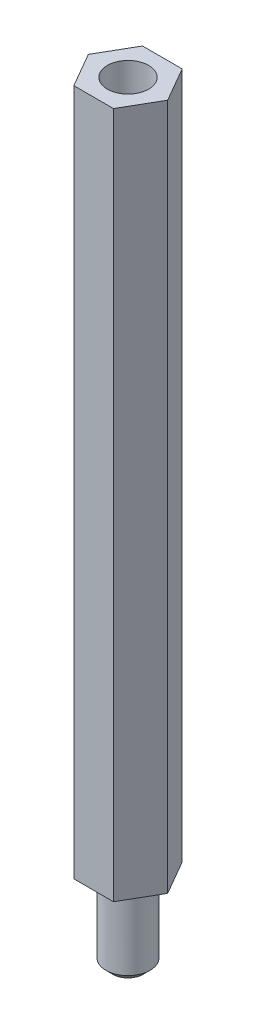
SolidWorks part; units mm, degrees
material "Alloy Steel"
ref_plane "Front Plane" through (0, 0, 0) normal (0, 0, 1) x (1, 0, 0)
ref_plane "Top Plane" through (0, 0, 0) normal (0, 1, 0) x (1, 0, 0)
ref_plane "Right Plane" through (0, 0, 0) normal (1, 0, 0) x (0, 0, -1)
sketch "Sketch1" plane through (0, 0, 0) normal (0, 1, 0) x (1, 0, 0)
  line L0 (0, 0) -> (0, 2.5) construction
  line L1 (-1.4434, 2.5) -> (1.4434, 2.5)
  line L2 (1.4434, 2.5) -> (2.8868, 0)
  line L3 (2.8868, 0) -> (1.4434, -2.5)
  line L4 (1.4434, -2.5) -> (-1.4434, -2.5)
  line L5 (-1.4434, -2.5) -> (-2.8868, 0)
  line L6 (-2.8868, 0) -> (-1.4434, 2.5)
  circle A0 centre (0, 0) radius 1.5
  dimension "D2" = 3
  dimension "D1" = 5
  dimension "D3" = 2.5
extrude "Extrude1" add sketch "Sketch1" along normal blind 50
sketch "Sketch2" plane through (0, 0, 0) normal (0, -1, 0) x (1, 0, 0)
  circle A0 centre (0, 0) radius 1.6
  dimension "D1" = 3.2
extrude "Extrude2" add sketch "Sketch2" along normal blind 6 and the other way blind 22
chamfer "Chamfer1" distance 0.5 angle 45 1 edges at (0, -6, -1.6)
fillet "Fillet1" radius 0.5 1 edges at (0, 0, 1.6)
fillet "Fillet2" radius 1 1 edges at (0, 22, -1.5)
